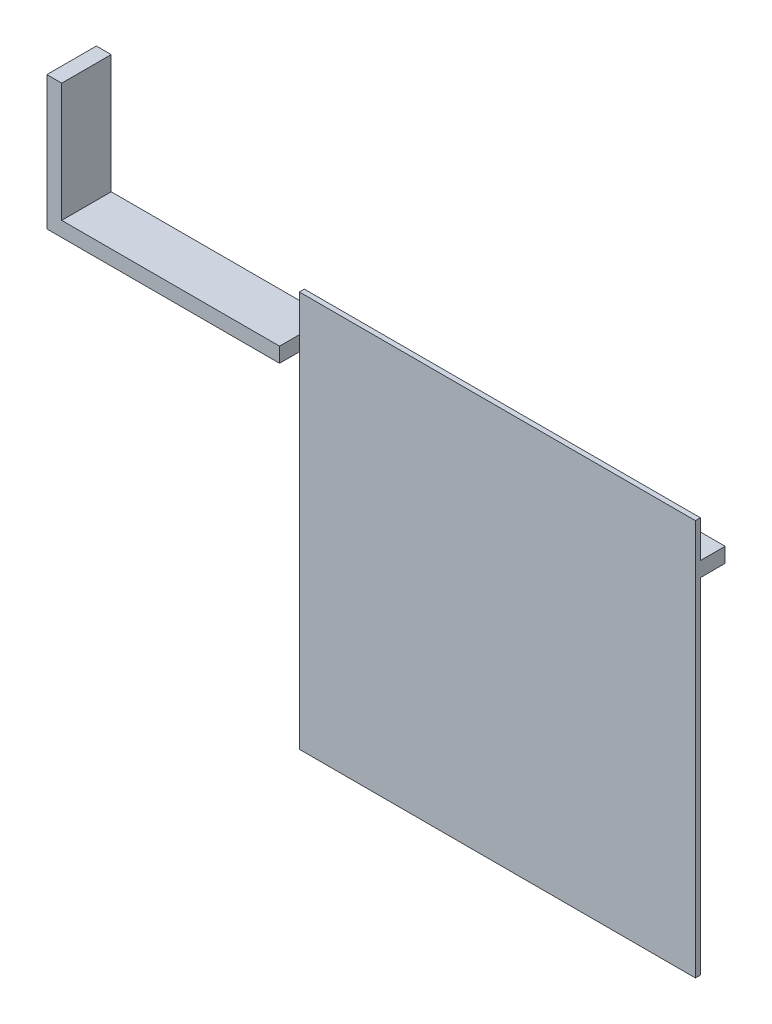
SolidWorks part; units mm, degrees
ref_plane "Front Plane" through (0, 0, 0) normal (0, 0, 1) x (1, 0, 0)
ref_plane "Top Plane" through (0, 0, 0) normal (0, 1, 0) x (1, 0, 0)
ref_plane "Right Plane" through (0, 0, 0) normal (1, 0, 0) x (0, 0, -1)
sketch "Sketch1" plane through (0, 0, 0) normal (0, 0, 1) x (1, 0, 0)
  line L0 (0, 0) -> (0, -27)
  line L1 (0, -27) -> (127, -27)
  line L2 (127, -27) -> (127, -24)
  line L3 (127, -24) -> (3, -24)
  line L4 (3, -24) -> (3, 0)
  line L5 (3, 0) -> (0, 0)
  dimension "D1" = 27
  dimension "D2" = 3
  dimension "D3" = 3
  dimension "D4" = 127
extrude "Boss-Extrude1" add sketch "Sketch1" along normal blind 10
sketch "Sketch4" plane through (0, -24, 0) normal (0, 1, 0) x (1, 0, 0)
  line L1 (127, -10) -> (47, -10)
  line L2 (127, -10) -> (127, -5)
  line L3 (127, -5) -> (47, -5)
  line L4 (47, -10) -> (47, -5)
  dimension "D1" = 5
  dimension "D2" = 80
extrude "Cut-Extrude1" cut sketch "Sketch4" against normal blind 6
sketch "Sketch5" plane through (0, 0, 5) normal (0, 0, 1) x (1, 0, 0)
  line L0 (127, -24) -> (47, -24) construction
  line L1 (47, -96.52) -> (127, -96.52)
  line L2 (47, -96.52) -> (47, -16.52)
  line L3 (47, -16.52) -> (127, -16.52)
  line L4 (127, -96.52) -> (127, -16.52)
  line L5 (47, -96.52) -> (127, -16.52) construction
  line L6 (47, -16.52) -> (127, -96.52) construction
  line L8 (127, -27) -> (127, -24) construction
  point P0 (87, -56.52)
  dimension "D1" = 32.52
  dimension "D2" = 80
  dimension "D3" = 80
  dimension "D4" = 40
extrude "Boss-Extrude3" add sketch "Sketch5" along normal blind 1
